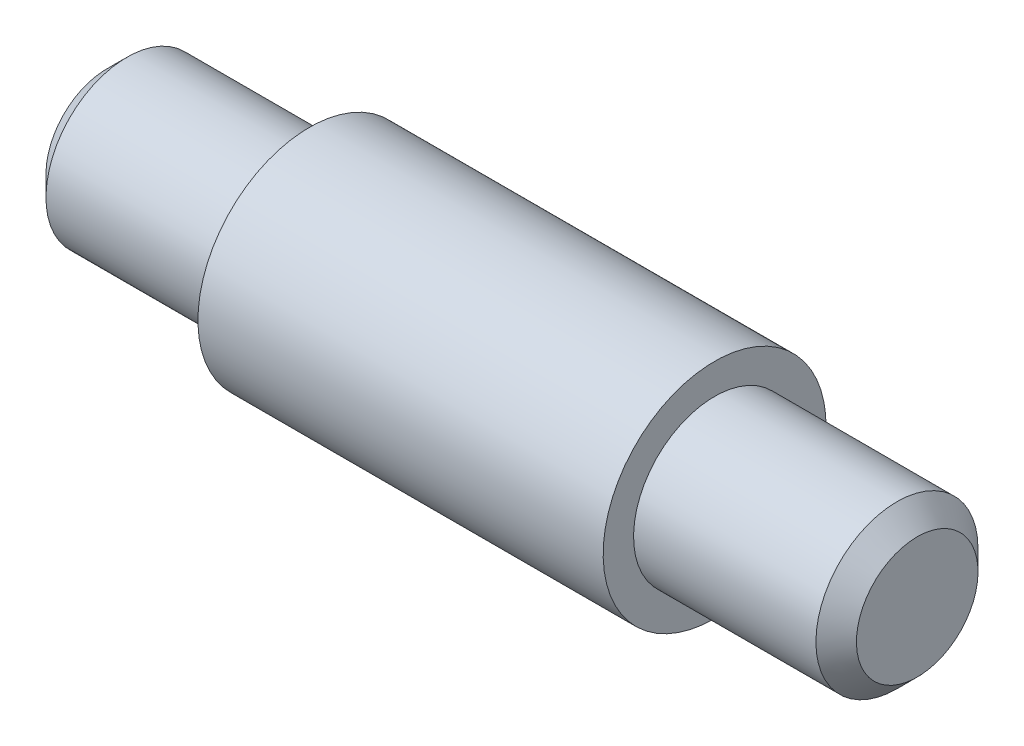
SolidWorks part; units mm, degrees
ref_plane "Plan de face" through (0, 0, 0) normal (0, 0, 1) x (1, 0, 0)
ref_plane "Plan de dessus" through (0, 0, 0) normal (0, 1, 0) x (1, 0, 0)
ref_plane "Plan de droite" through (0, 0, 0) normal (1, 0, 0) x (0, 0, -1)
sketch "Esquisse1" plane through (0, 0, 0) normal (0, 0, 1) x (1, 0, 0)
  line L0 (-50, 0) -> (50, 0) construction
  line L1 (40, 0) -> (40, -8)
  line L2 (40, -8) -> (20, -8)
  line L3 (20, -8) -> (20, -11)
  line L4 (20, -11) -> (-20, -11)
  line L5 (-20, -11) -> (-20, -8)
  line L6 (-20, -8) -> (-40, -8)
  line L7 (-40, -8) -> (-40, 0)
  line L8 (40, 0) -> (-40, 0)
  point P2 (0, 0)
  point P13 (0, -11)
  dimension "D1" = 100
  dimension "D2" = 8
  dimension "D3" = 11
  dimension "D4" = 40
  dimension "D6" = 20
  dimension "D7" = 80
revolve "Révolution1" add sketch "Esquisse1" angle 360 about L0
chamfer "Chanfrein1" distance 2 angle 45 2 edges at (40, -8, 0) (-40, -8, 0)
